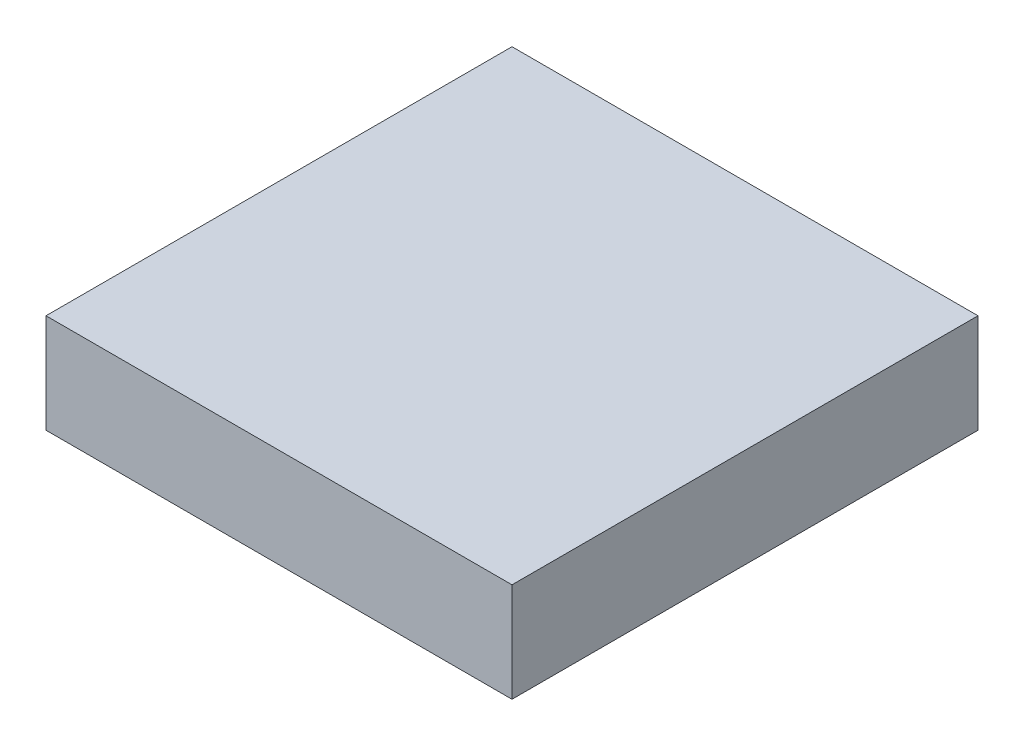
SolidWorks part; units mm, degrees
ref_plane "Front Plane" through (0, 0, 0) normal (0, 0, 1) x (1, 0, 0)
ref_plane "Top Plane" through (0, 0, 0) normal (0, 1, 0) x (1, 0, 0)
ref_plane "Right Plane" through (0, 0, 0) normal (1, 0, 0) x (0, 0, -1)
sketch "Sketch4" plane through (0, 0, 0) normal (0, 1, 0) x (1, 0, 0)
  line L1 (-39.6184, 101.9268) -> (79.7616, 101.9268)
  line L2 (-39.6184, 101.9268) -> (-39.6184, -17.4532)
  line L3 (-39.6184, -17.4532) -> (79.7616, -17.4532)
  line L4 (79.7616, 101.9268) -> (79.7616, -17.4532)
  dimension "D1" = 119.38
  dimension "D2" = 119.38
extrude "Boss-Extrude2" add sketch "Sketch4" along normal blind 25.4
sketch "Sketch5" plane through (0, 25.4, 0) normal (0, 1, 0) x (1, 0, 0)
  line L0 (-39.6184, 42.2368) -> (79.7616, 42.2368) construction
  line L1 (-39.6184, 101.9268) -> (-39.6184, -17.4532) construction
  line L2 (79.7616, -17.4532) -> (79.7616, 101.9268) construction
  line L3 (20.0716, 101.9268) -> (20.0716, -17.4532) construction
  line L4 (79.7616, 101.9268) -> (-39.6184, 101.9268) construction
  line L5 (-39.6184, -17.4532) -> (79.7616, -17.4532) construction
  line L7 (-32.3794, -10.2142) -> (72.5226, -10.2142)
  line L8 (-32.3794, -10.2142) -> (-32.3794, 94.6878)
  line L9 (-32.3794, 94.6878) -> (72.5226, 94.6878)
  line L10 (72.5226, -10.2142) -> (72.5226, 94.6878)
  line L11 (-32.3794, -10.2142) -> (72.5226, 94.6878) construction
  line L12 (-32.3794, 94.6878) -> (72.5226, -10.2142) construction
  circle A0 centre (20.0716, 42.2368) radius 57.5499
  circle A1 centre (-32.3794, 94.6878) radius 2.159
  circle A2 centre (72.5226, 94.6878) radius 2.159
  circle A3 centre (72.5226, -10.2142) radius 2.159
  circle A4 centre (-32.3794, -10.2142) radius 2.159
  circle A5 centre (20.0716, 42.2368) radius 67.5607
  point P12 (20.0716, 42.2368)
  dimension "D3" = 4.318
  dimension "D4" = 4.318
  dimension "D5" = 4.318
  dimension "D6" = 4.318
  dimension "D1" = 104.902
  dimension "D2" = 104.902
